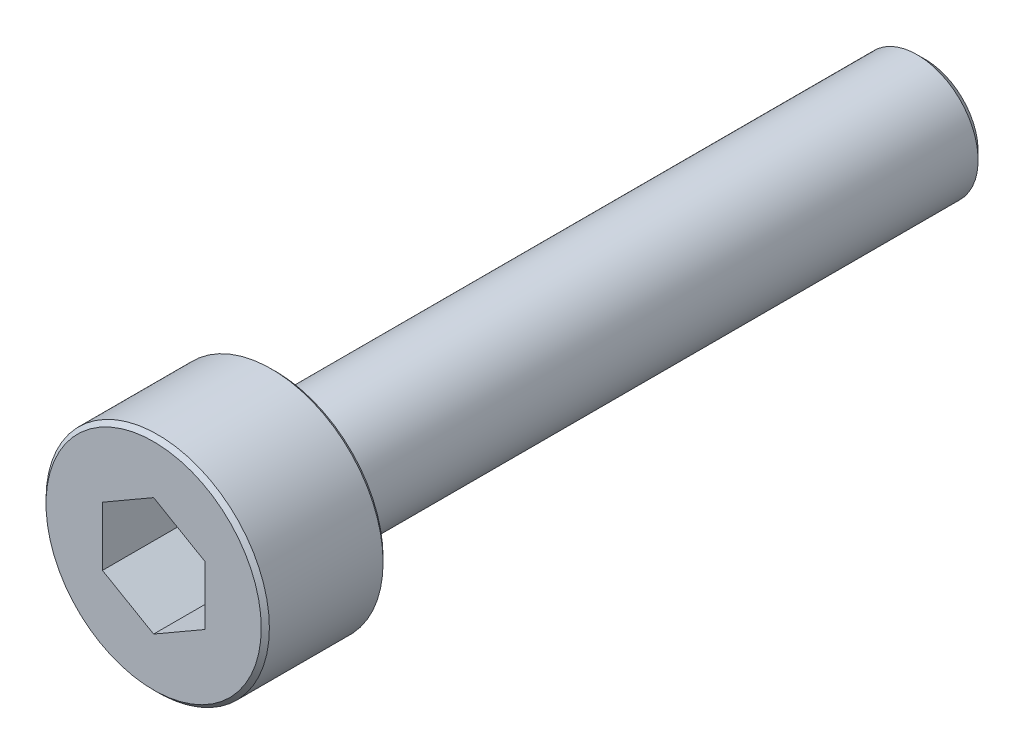
SolidWorks part; units mm, degrees
ref_plane "前视基准面" through (0, 0, 0) normal (0, 0, 1) x (1, 0, 0)
ref_plane "上视基准面" through (0, 0, 0) normal (0, 1, 0) x (1, 0, 0)
ref_plane "右视基准面" through (0, 0, 0) normal (1, 0, 0) x (0, 0, -1)
other "Configuration Table"
sketch "草图1" plane through (0, 0, 0) normal (0, 1, 0) x (1, 0, 0)
  line L0 (2.75, -16) -> (0, -16)
  line L1 (0, -16) -> (0, -19)
  line L2 (0, -19) -> (2.75, -19)
  line L3 (2.75, -19) -> (2.75, -16)
  line L4 (0, -16) -> (0, -19) construction
revolve "旋转1" add sketch "草图1" angle 360 about L4
sketch "草图2" plane through (0, 0, 16) normal (0, 0, -1) x (-1, 0, 0)
  circle A0 centre (0, 0) radius 1.5
extrude "凸台-拉伸1" add sketch "草图2" along normal blind 16
sketch "草图3" plane through (0, 0, 19) normal (0, 0, 1) x (1, 0, 0)
  line L0 (-1.26, -0.7275) -> (0, -1.4549)
  line L1 (0, -1.4549) -> (1.26, -0.7275)
  line L2 (1.26, -0.7275) -> (1.26, 0.7275)
  line L3 (1.26, 0.7275) -> (0, 1.4549)
  line L4 (0, 1.4549) -> (-1.26, 0.7275)
  line L5 (-1.26, 0.7275) -> (-1.26, -0.7275)
extrude "切除-拉伸1" cut sketch "草图3" against normal blind 2.25
chamfer "倒角1" distance 0.1 angle 45 2 edges at (2.75, 0, 16) (2.75, 0, 19)
chamfer "倒角2" distance 0.2 angle 45 1 edges at (-1.5, 0, 0)
